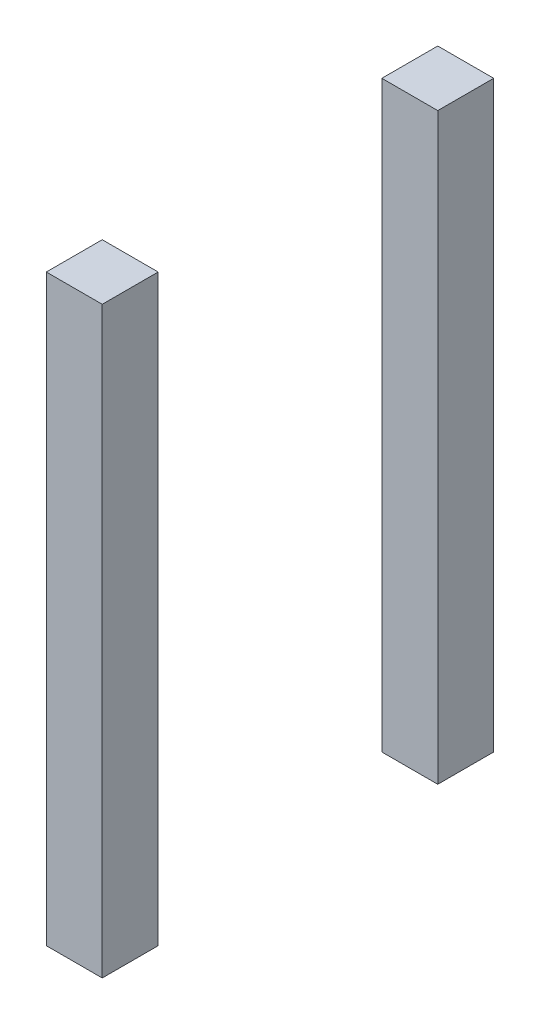
SolidWorks part; units mm, degrees
ref_plane "Front Plane" through (0, 0, 0) normal (0, 0, 1) x (1, 0, 0)
ref_plane "Top Plane" through (0, 0, 0) normal (0, 1, 0) x (1, 0, 0)
ref_plane "Right Plane" through (0, 0, 0) normal (1, 0, 0) x (0, 0, -1)
sketch "Sketch1" plane through (0, -45.0089, 0) normal (0, 1, 0) x (1, 0, 0)
  line L0 (-76.7059, -45.7179) -> (-67.1809, -45.7179) construction
  line L1 (-76.7059, -40.9554) -> (-76.7059, -50.4804) construction
  line L2 (-71.9434, -50.4804) -> (-71.9434, -40.9554) construction
  line L3 (-67.1809, -40.9554) -> (-76.7059, -40.9554) construction
  line L4 (-67.3079, 5.2726) -> (-76.5789, 14.5436) construction
  line L5 (-67.3079, -50.3534) -> (-76.5789, -50.3534)
  line L7 (-67.1809, -50.4804) -> (-67.1809, -40.9554) construction
  line L8 (-83.1991, -17.9049) -> (10.7809, -17.9049) construction
  line L9 (-83.1991, -64.8949) -> (-83.1991, 29.0851) construction
  line L10 (10.7809, 29.0851) -> (10.7809, -64.8949) construction
  line L11 (-76.7059, -50.4804) -> (-67.1809, -50.4804) construction
  line L12 (-67.3079, -50.3534) -> (-67.3079, -41.0824)
  line L13 (-67.3079, -41.0824) -> (-76.5789, -41.0824)
  line L14 (-76.5789, -50.3534) -> (-76.5789, -41.0824)
  line L15 (-67.3079, -50.3534) -> (-76.5789, -41.0824) construction
  line L16 (-67.3079, -41.0824) -> (-76.5789, -50.3534) construction
  line L17 (-67.3079, 14.5436) -> (-76.5789, 5.2726) construction
  line L18 (-71.9434, 14.6706) -> (-71.9434, 5.1456) construction
  line L19 (-76.7059, 9.9081) -> (-67.1809, 9.9081) construction
  line L20 (-76.5789, 14.5436) -> (-76.5789, 5.2726)
  line L21 (-67.3079, 5.2726) -> (-76.5789, 5.2726)
  line L22 (-67.3079, 14.5436) -> (-67.3079, 5.2726)
  line L23 (-67.3079, 14.5436) -> (-76.5789, 14.5436)
  point P10 (-71.9434, -45.7179)
  point P33 (-71.9434, 9.9081)
  dimension "D1" = 0.127
extrude "Boss-Extrude1" add sketch "Sketch1" along normal up to surface (96.7317 mm away)
